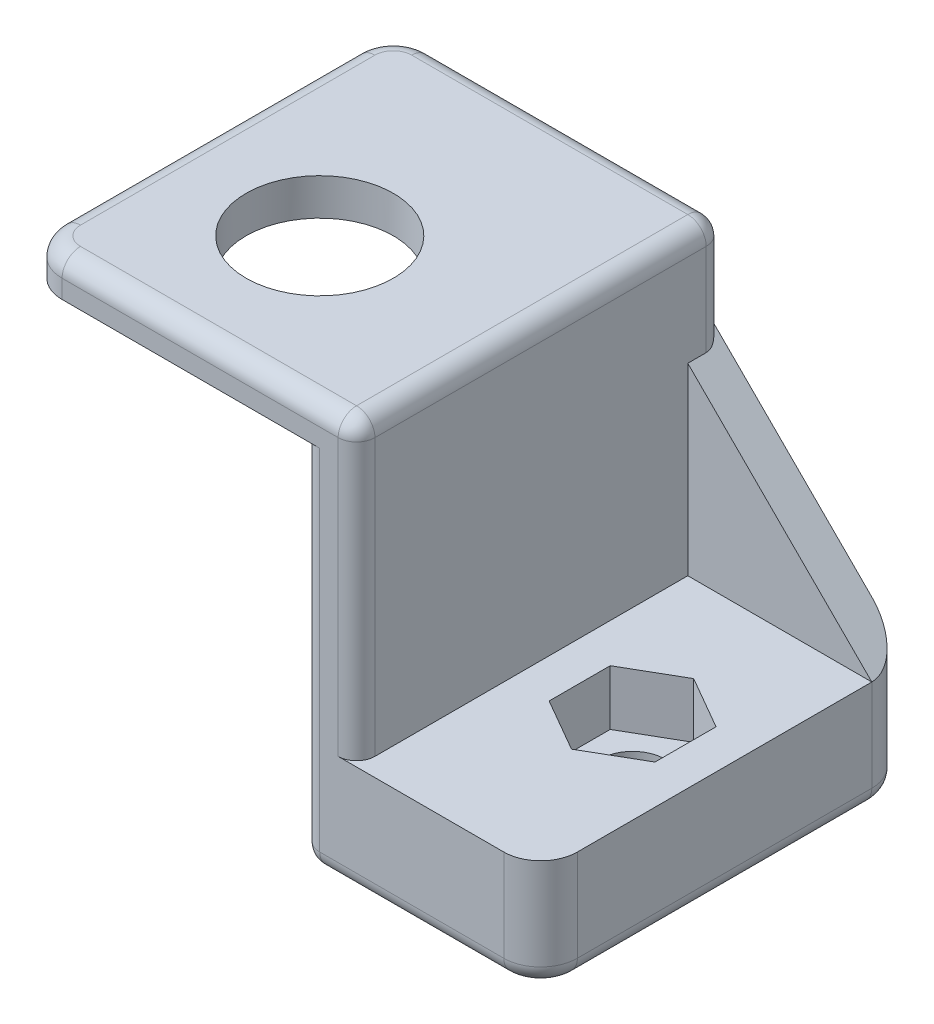
SolidWorks part; units mm, degrees
ref_plane "Front Plane" through (0, 0, 0) normal (0, 0, 1) x (1, 0, 0)
ref_plane "Top Plane" through (0, 0, 0) normal (0, 1, 0) x (1, 0, 0)
ref_plane "Right Plane" through (0, 0, 0) normal (1, 0, 0) x (0, 0, -1)
sketch "Sketch1" plane through (0, 0, 0) normal (0, 0, 1) x (1, 0, 0)
  line L0 (0, 0) -> (0, 40)
  line L1 (0, 40) -> (-30, 40)
  line L2 (-30, 40) -> (-30, 44)
  line L3 (-30, 44) -> (6, 44)
  line L4 (6, 44) -> (6, 12)
  line L5 (6, 12) -> (26, 12)
  line L6 (26, 12) -> (26, 0)
  line L7 (26, 0) -> (0, 0)
  dimension "D1" = 4
  dimension "D2" = 36
  dimension "D3" = 20
  dimension "D4" = 12
  dimension "D5" = 6
  dimension "D6" = 40
extrude "Boss-Extrude1" add sketch "Sketch1" along normal blind 40
sketch "Sketch3" plane through (0, 12, 0) normal (0, 1, 0) x (1, 0, 0)
  line L0 (16, -20) -> (26, -20) construction
  line L1 (26, -40) -> (26, 0) construction
  line L2 (16, -20) -> (6, -20) construction
  line L3 (6, -40) -> (6, 0) construction
  line L4 (16, -20) -> (16, 0) construction
  line L5 (26, 0) -> (6, 0) construction
  line L6 (16, -20) -> (16, -40) construction
  line L7 (26, -40) -> (6, -40) construction
  circle A0 centre (16, -20) radius 3.5
  dimension "D1" = 7
extrude "Cut-Extrude1" cut sketch "Sketch3" against normal blind 32
sketch "Sketch2" plane through (0, 44, 0) normal (0, 1, 0) x (1, 0, 0)
  line L0 (-30, -40) -> (-30, 0) construction
  line L3 (6, -40) -> (-30, -40) construction
  circle A0 centre (-14, -24) radius 8
  dimension "D1" = 16
  dimension "D2" = 16
  dimension "D3" = 16
extrude "Cut-Extrude2" cut sketch "Sketch2" against normal blind 32
sketch "Sketch4" plane through (0, 12, 0) normal (0, 1, 0) x (1, 0, 0)
  line L0 (26, -40) -> (26, 0) construction
  line L1 (16, -26.6395) -> (21.75, -23.3198)
  line L2 (21.75, -23.3198) -> (21.75, -16.6802)
  line L3 (21.75, -16.6802) -> (16, -13.3605)
  line L4 (16, -13.3605) -> (10.25, -16.6802)
  line L5 (10.25, -16.6802) -> (10.25, -23.3198)
  line L6 (10.25, -23.3198) -> (16, -26.6395)
  circle A0 centre (16, -20) radius 5.75 construction
  dimension "D1" = 11.5
extrude "Cut-Extrude3" cut sketch "Sketch4" against normal blind 6
sketch "Sketch5" plane through (0, 0, 0) normal (0, 0, -1) x (-1, 0, 0)
  line L0 (-26, 12) -> (-6, 32)
  line L1 (-6, 32) -> (-6, 12)
  line L2 (-6, 12) -> (-26, 12)
  line L3 (0, 10) -> (0, 40)
  line L4 (0, 40) -> (30, 40)
  line L5 (30, 40) -> (0, 10)
  line L6 (-6, 12) -> (-6, 44) construction
  line L7 (0, 40) -> (0, 0) construction
  dimension "D1" = 30
  dimension "D2" = 20
extrude "Boss-Extrude3" add sketch "Sketch5" against normal blind 4
fillet "Fillet1" radius 4 4 edges at (26, 6, 40) (26, 6, 0) (-30, 42, 40) (-30, 42, 0)
fillet "Fillet4" radius 2 15 edges at (11, 0, 40) (24.8284, 0, 38.8284) (11, 0, 0) (24.8284, 0, 1.1716) (-10, 44, 0) (-28.8284, 44, 1.1716) (-30, 44, 20) (-28.8284, 44, 38.8284) (6, 38, 0) (0, 20, 40) (26, 0, 20) (0, 0, 20) (-10, 44, 40) (6, 28, 40) (6, 44, 20)
